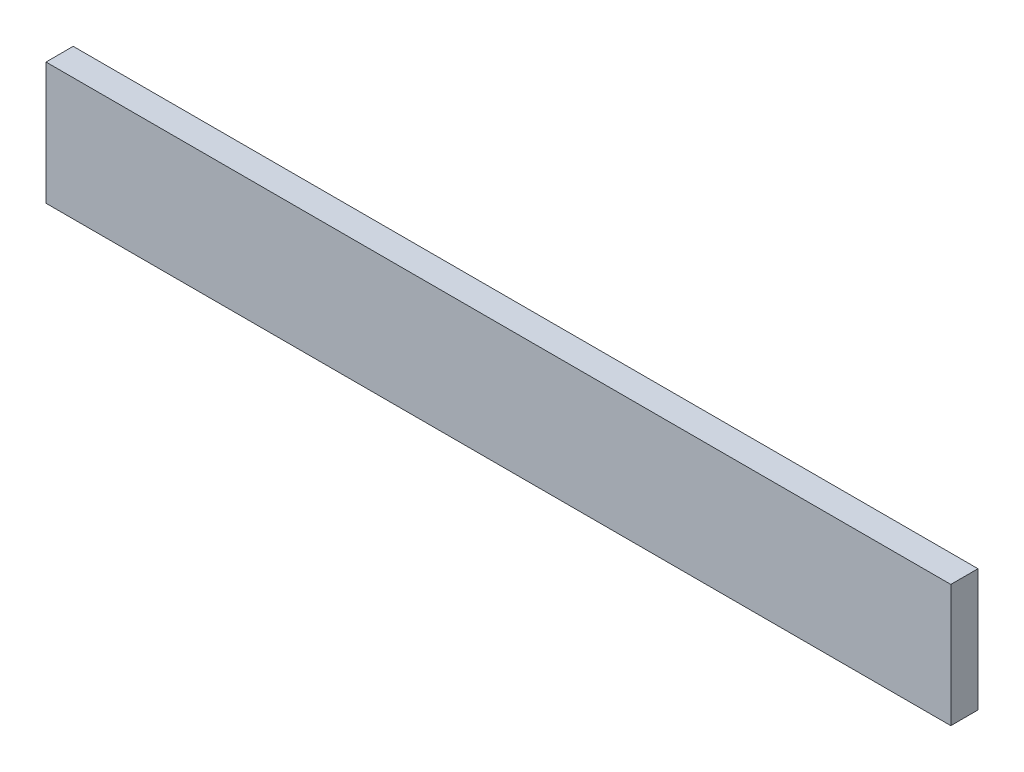
SolidWorks part; units mm, degrees
ref_plane "前视基准面" through (0, 0, 0) normal (0, 0, 1) x (1, 0, 0)
ref_plane "上视基准面" through (0, 0, 0) normal (0, 1, 0) x (1, 0, 0)
ref_plane "右视基准面" through (0, 0, 0) normal (1, 0, 0) x (0, 0, -1)
sketch "草图1" plane through (0, 0, 0) normal (0, 0, 1) x (1, 0, 0)
  line L0 (0, -5) -> (-166.4, -5)
  line L1 (21, -5) -> (-21, -5) construction
  line L2 (-166.4, 79.3231) -> (-166.4, -40.6769) construction
  line L3 (-166.4, -5) -> (-166.4, -50)
  line L4 (-166.4, -50) -> (166.4, -50)
  line L5 (166.4, 79.3231) -> (166.4, -40.6769) construction
  line L6 (166.4, -50) -> (166.4, -5)
  line L7 (166.4, -5) -> (0, -5)
  dimension "D1" = 45
extrude "凸台-拉伸1" add sketch "草图1" along normal blind 10
